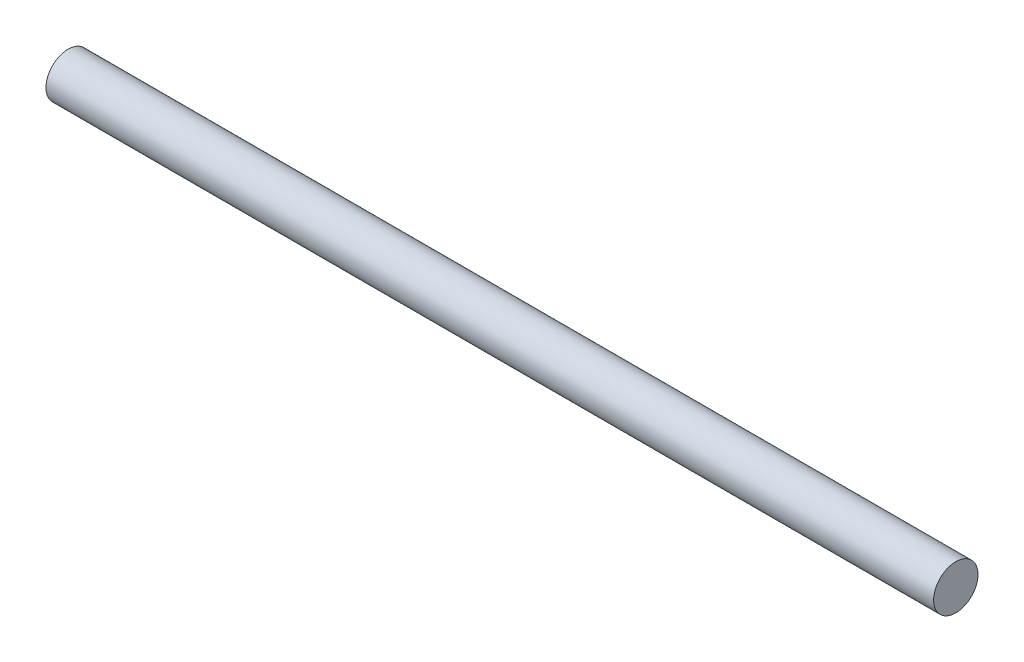
SolidWorks part; units mm, degrees
ref_plane "Front Plane" through (0, 0, 0) normal (0, 0, 1) x (1, 0, 0)
ref_plane "Top Plane" through (0, 0, 0) normal (0, 1, 0) x (1, 0, 0)
ref_plane "Right Plane" through (0, 0, 0) normal (1, 0, 0) x (0, 0, -1)
sketch "Sketch1" plane through (0, 0, 0) normal (1, 0, 0) x (0, 0, -1)
  circle A0 centre (0, 0) radius 3.175
  dimension "D1" = 6.35
extrude "Boss-Extrude1" add sketch "Sketch1" along normal blind 127 contours A0
